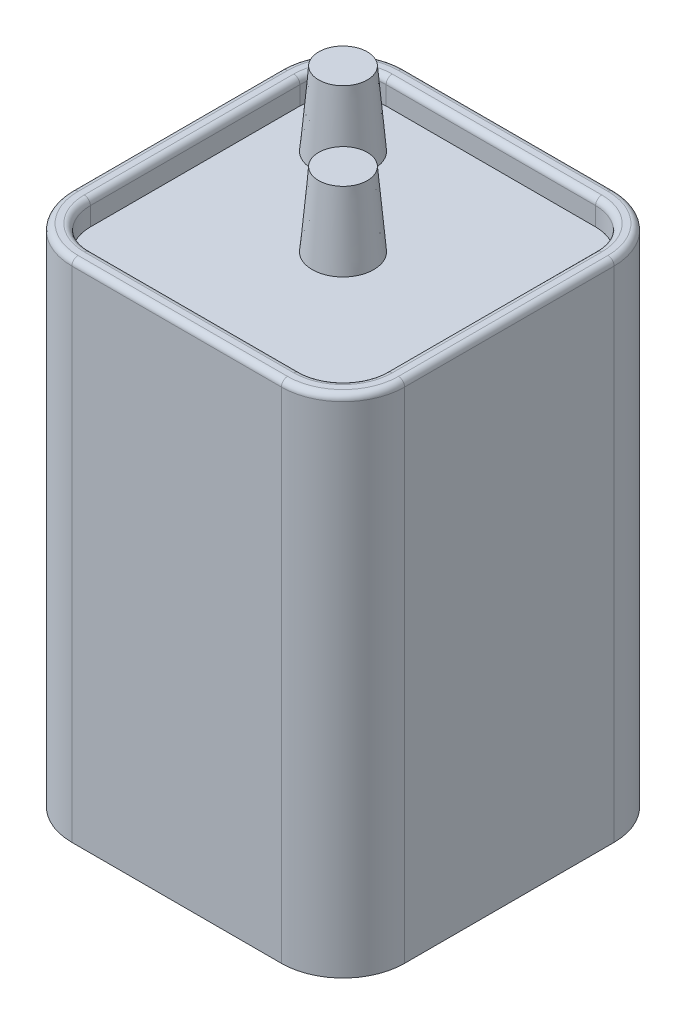
SolidWorks part; units mm, degrees
ref_plane "Front Plane" through (0, 0, 0) normal (0, 0, 1) x (1, 0, 0)
ref_plane "Top Plane" through (0, 0, 0) normal (0, 1, 0) x (1, 0, 0)
ref_plane "Right Plane" through (0, 0, 0) normal (1, 0, 0) x (0, 0, -1)
sketch "Sketch1" plane through (0, 0, 0) normal (0, 1, 0) x (1, 0, 0)
  line L1 (-34.29, 34.29) -> (34.29, 34.29)
  line L2 (-34.29, 34.29) -> (-34.29, -34.29)
  line L3 (-34.29, -34.29) -> (34.29, -34.29)
  line L4 (34.29, 34.29) -> (34.29, -34.29)
  line L5 (-34.29, 34.29) -> (34.29, -34.29) construction
  line L6 (-34.29, -34.29) -> (34.29, 34.29) construction
  point P0 (0, 0)
  dimension "D1" = 68.58
  dimension "D2" = 68.58
extrude "Base Extrude" add sketch "Sketch1" along normal blind 104.14
fillet "Side Fillets" radius 12.7 4 edges at (-34.29, 52.07, -34.29) (-34.29, 52.07, 34.29) (34.29, 52.07, -34.29) (34.29, 52.07, 34.29)
sketch "Sketch3" plane through (0, 104.14, 0) normal (0, 1, 0) x (1, 0, 0)
  line L12 (21.59, 30.48) -> (-21.59, 30.48)
  line L13 (-30.48, 21.59) -> (-30.48, -21.59)
  line L14 (-21.59, -30.48) -> (21.59, -30.48)
  line L15 (30.48, -21.59) -> (30.48, 21.59)
  line L16 (21.59, 30.48) -> (-21.59, 30.48)
  line L17 (-30.48, 21.59) -> (-30.48, -21.59)
  line L18 (-21.59, -30.48) -> (21.59, -30.48)
  line L19 (30.48, -21.59) -> (30.48, 21.59)
  arc A12 (-21.59, 30.48) -> (-30.48, 21.59) centre (-21.59, 21.59) ccw
  arc A13 (-30.48, -21.59) -> (-21.59, -30.48) centre (-21.59, -21.59) ccw
  arc A14 (21.59, -30.48) -> (30.48, -21.59) centre (21.59, -21.59) ccw
  arc A15 (30.48, 21.59) -> (21.59, 30.48) centre (21.59, 21.59) ccw
  arc A16 (-21.59, 30.48) -> (-30.48, 21.59) centre (-21.59, 21.59) ccw
  arc A17 (-30.48, -21.59) -> (-21.59, -30.48) centre (-21.59, -21.59) ccw
  arc A18 (21.59, -30.48) -> (30.48, -21.59) centre (21.59, -21.59) ccw
  arc A19 (30.48, 21.59) -> (21.59, 30.48) centre (21.59, 21.59) ccw
  dimension "D1" = 3.81
extrude "Top Cut" cut sketch "Sketch3" against normal blind 5.08
fillet "Top Face Fillet" radius 1.27 16 edges at (30.5703, 104.14, -30.5703) (34.29, 104.14, 0) (30.5703, 104.14, 30.5703) (0, 104.14, 34.29) (-30.5703, 104.14, 30.5703) (-34.29, 104.14, 0) (-30.5703, 104.14, -30.5703) (0, 104.14, -34.29) (0, 104.14, -30.48) (-27.8762, 104.14, -27.8762) (-30.48, 104.14, 0) (-27.8762, 104.14, 27.8762) (0, 104.14, 30.48) (27.8762, 104.14, 27.8762) (30.48, 104.14, 0) (27.8762, 104.14, -27.8762)
sketch "Sketch-Terminals" plane through (0, 99.06, 0) normal (0, 1, 0) x (1, 0, 0)
  line L0 (-17.9605, 17.9605) -> (0, 0) construction
  line L1 (0, -37.719) -> (0, 37.719) construction
  circle A0 centre (0, 0) radius 6.35
  circle A1 centre (-17.9605, 17.9605) radius 6.35
  dimension "D1" = 12.7
  dimension "D2" = 25.4
  dimension "D3" = 45
extrude "Terminals" add sketch "Sketch-Terminals" along normal blind 15.24 draft 5
